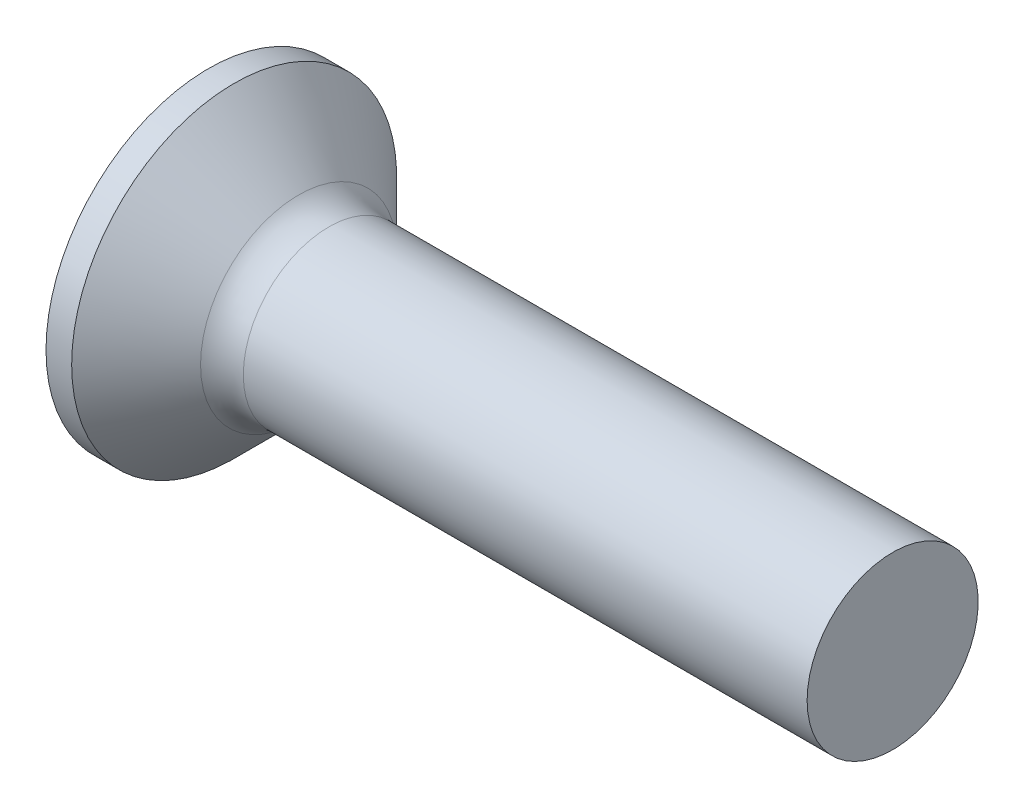
SolidWorks part; units mm, degrees
ref_plane "Plane1" through (0, 0, 0) normal (0, 0, 1) x (1, 0, 0)
ref_plane "Plane2" through (0, 0, 0) normal (0, 1, 0) x (1, 0, 0)
ref_plane "Plane3" through (0, 0, 0) normal (1, 0, 0) x (0, 0, -1)
sketch "BodySke" plane through (0, 0, 0) normal (0, 0, 1) x (1, 0, 0)
  line L0 (0, 0) -> (0, 1.9)
  line L1 (0, 1.9) -> (0.3, 1.9)
  line L2 (1.2, 1) -> (8, 1)
  line L3 (8, 1) -> (8, 0)
  line L4 (8, 0) -> (0, 0)
  line L5 (-6.35, 0) -> (82.55, 0) construction
  line L6 (1.2, -1) -> (8, -1) construction
  line L7 (0.3, -1.9) -> (1.2, -1) construction
  line L8 (0.3, 1.9) -> (1.2, 1)
  line L9 (0, -1.9) -> (0.3, -1.9) construction
  line L10 (1.6, 2.5875) -> (1.6, -6.9375) construction
  line L11 (0, 6.35) -> (0, -3.175) construction
  dimension "Diameter" = 2
  dimension "Length" = 8
  dimension "Head_ht" = 1.2
  dimension "Head_dia" = 3.8
  dimension "Head_ang" = 90
  dimension "D6" = 0.3
  dimension "Advance" = 0.4
  dimension "Thread_nom" = 8
revolve "Base-Revolve" add sketch "BodySke"
cosmetic thread "ThreadCosmetic" [suppressed]
fillet "Fillet1" radius 0.5 1 edges at (1.2, 0, 1)
sketch "Sketch3" plane through (0, 0, 0) normal (-1, 0, 0) x (0, 0, 1)
  line L0 (-0.24, 0.95) -> (0.24, 0.95)
  line L1 (0.24, 0.95) -> (0.24, -0.95)
  line L2 (0.24, -0.95) -> (-0.24, -0.95)
  line L3 (-0.24, -0.95) -> (-0.24, 0.95)
  dimension "D1" = 0.95
  dimension "Cross_dia" = 1.9
  dimension "D2" = 0.24
  dimension "Cross_width" = 0.48
ref_plane "Plane4" through (1.2, 0, 0) normal (-1, 0, 0) x (0, 0, 1)
sketch "Sketch4" plane through (1.2, 0, 0) normal (-1, 0, 0) x (0, 0, 1)
  line L0 (-0.24, 0.3517) -> (0.24, 0.3517)
  line L3 (0.24, 0.3517) -> (0.24, -0.3517)
  line L4 (0.24, -0.3517) -> (-0.24, -0.3517)
  line L5 (-0.24, -0.3517) -> (-0.24, 0.3517)
  dimension "D1" = 0.48
  dimension "D2" = 0.7034
  dimension "D3" = 0.24
  dimension "D4" = 0.3517
loft "Recess" cut profiles "Sketch3", "Sketch4"
pattern_circular "RecPat" count 2 every 90 about axis through (0, 0, 0) along (1, 0, 0) of "Recess"
sketch "RecCorSke" plane through (0, 0, 0) normal (0, 0, 1) x (1, 0, 0)
  line L0 (-3.175, 0) -> (15.875, 0) construction
  line L2 (0, 0) -> (0, 0.4394)
  line L3 (0, 0.4394) -> (1.2, 0.3555)
  line L4 (1.2, 0.3555) -> (1.3155, 0)
  line L5 (1.3155, 0) -> (0, 0)
  dimension "Diameter" = 0.711
  dimension "Depth" = 1.2
  dimension "Draft_angle" = 4
  dimension "Bottom_angle" = 18
revolve "RecessCore" cut sketch "RecCorSke" angle 360 about L0
sketch "ThdSchSke" plane through (0, 0, 0) normal (0, 0, 1) x (1, 0, 0)
  line L0 (1.6, -0.774) -> (1.4418, -1)
  line L1 (1.6, -0.774) -> (1.7582, -1)
  line L2 (1.7582, -1) -> (1.7582, -1.25)
  line L3 (-3.175, 0) -> (5.1513, 0) construction
  line L5 (1.7582, -1.25) -> (1.4418, -1.25)
  line L6 (1.4418, -1.25) -> (1.4418, -1)
  line L7 (0, 1.9) -> (0, -1.9) construction
  dimension "Thread_minor" = 1.548
  dimension "Diameter" = 2
  dimension "Start" = 1.6
  dimension "SideAngle" = 55
  dimension "VeeAngle" = 70
  dimension "Overcut" = 2.5
revolve "ThreadSchematic" [suppressed] cut sketch "ThdSchSke" angle 360 about L3
pattern_linear "ThdSchPat" [suppressed]
equation "\"D1@Sketch3\" = \"Cross_dia@Sketch3\" / 2"
equation "\"D2@Sketch3\" = \"Cross_width@Sketch3\" / 2"
equation "\"Depth@RecCorSke\" = \"Cross_depth@Plane4\""
equation "\"D1@Sketch4\" = \"Cross_width@Sketch3\""
equation "\"D2@Sketch4\" = \"Cross_dia@Sketch3\" - 2.0 * \"Cross_depth@Plane4\" * tan(26.5  * 0.017453292)"
equation "\"D3@Sketch4\" = \"D1@Sketch4\" / 2"
equation "\"D4@Sketch4\" = \"D2@Sketch4\" / 2"
equation "\"Thread_length@ThreadCosmetic\" = ((sgn( (\"Length@BodySke\" - \"Advance@BodySke\" * 1.0 - \"Head_ht@BodySke\" ) - \"Thread_nom@BodySke\" )-1)*( (\"Length@BodySke\" - \"Advance@BodySke\" * 1.0 - \"Head_ht@BodySke\" ) - \"Thread_nom@BodySke\" ))/-2+ \"Thread_nom@BodySke\""
equation "\"Thread_minor@ThdSchSke\" = \"Thread_minor@ThreadCosmetic\""
equation "\"Diameter@ThdSchSke\" = \"Diameter@BodySke\""
equation "\"Overcut@ThdSchSke\" = \"Diameter@BodySke\" * 1.25"
equation "\"Start@ThdSchSke\" = 0.000001 + \"Length@BodySke\" - \"Thread_length@ThreadCosmetic\"  '---Countersunk---"
equation "\"Num_threads@ThdSchPat\" = int( \"Thread_length@ThreadCosmetic\" / \"Advance@BodySke\" + 0.999 )  + 1"
equation "\"Advance@ThdSchPat\" = \"Thread_length@ThreadCosmetic\" /  (\"Num_threads@ThdSchPat\" - 1) 'relax it"
